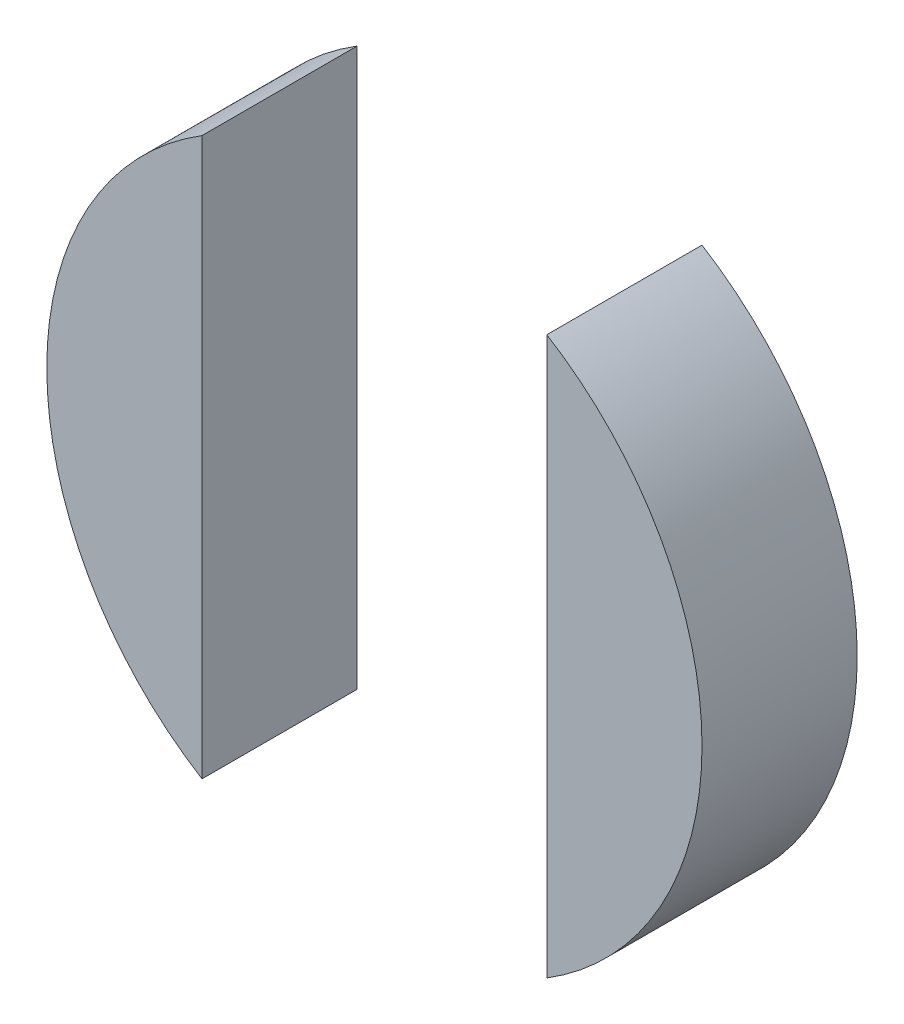
SolidWorks part; units mm, degrees
ref_plane "Front Plane" through (0, 0, 0) normal (0, 0, 1) x (1, 0, 0)
ref_plane "Top Plane" through (0, 0, 0) normal (0, 1, 0) x (1, 0, 0)
ref_plane "Right Plane" through (0, 0, 0) normal (1, 0, 0) x (0, 0, -1)
sketch "Sketch1" plane through (0, 0, 0) normal (0, 0, 1) x (1, 0, 0)
  line L0 (-5, 8.0777) -> (-5, -8.0777)
  line L1 (5, 8.0777) -> (5, -8.0777)
  circle A0 centre (0, 0) radius 9.5 construction
  arc A2 (-5, 8.0777) -> (-5, -8.0777) centre (0, 0) ccw
  arc A3 (5, 8.0777) -> (5, -8.0777) centre (0, 0) cw
  dimension "D1" = 19
  dimension "D3" = 5
  dimension "D4" = 5
extrude "Boss-Extrude1" add sketch "Sketch1" along normal blind 4.5
